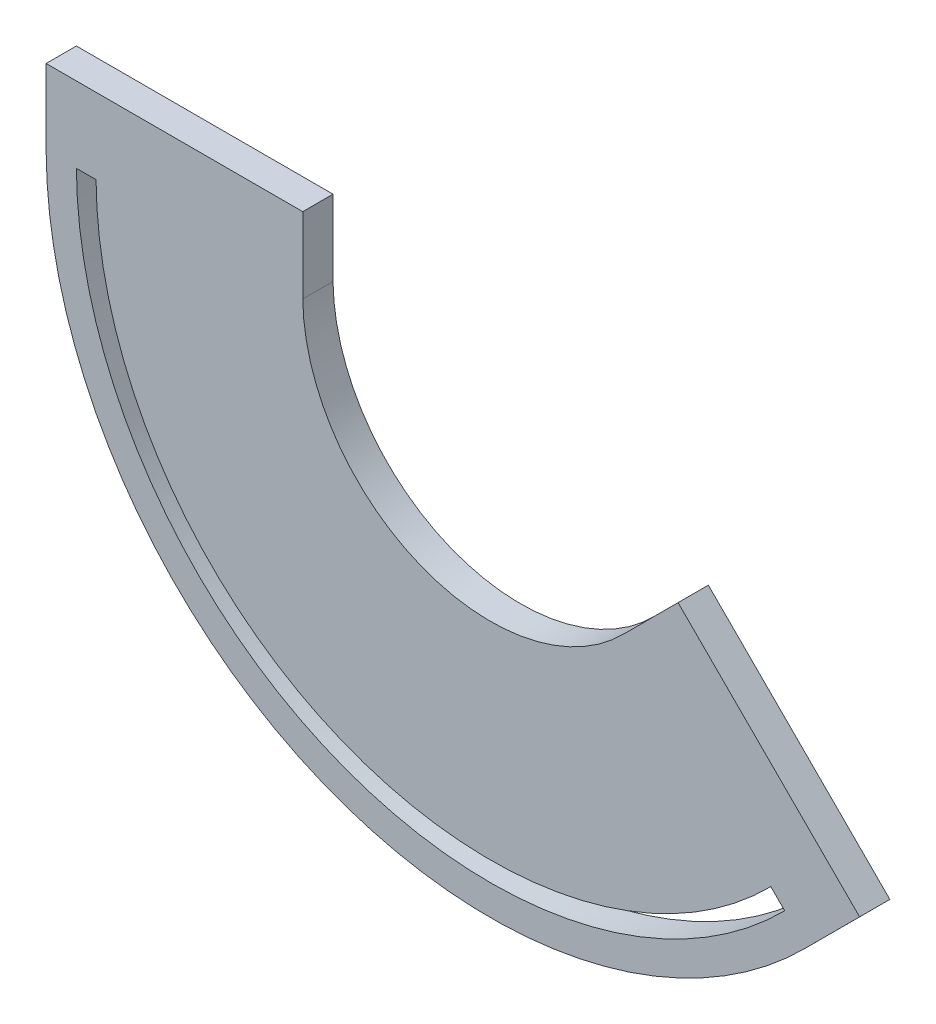
SolidWorks part; units mm, degrees
ref_plane "Front Plane" through (0, 0, 0) normal (0, 0, 1) x (1, 0, 0)
ref_plane "Top Plane" through (0, 0, 0) normal (0, 1, 0) x (1, 0, 0)
ref_plane "Right Plane" through (0, 0, 0) normal (1, 0, 0) x (0, 0, -1)
sketch "Sketch2" plane through (0, 0, 0) normal (0, 0, 1) x (1, 0, 0)
  line L0 (22.5377, -22.0011) -> (53.0117, -52.4532) construction
  line L1 (-74.575, -0.3794) -> (-31.4937, -0.3794) construction
  line L2 (22.5377, -22.0011) -> (31.5148, -13.0176)
  line L3 (31.5148, -13.0176) -> (61.9887, -43.4698)
  line L4 (53.0117, -52.4532) -> (61.9887, -43.4698)
  line L6 (-74.575, -0.3794) -> (-31.4937, -0.3794) construction
  line L7 (-74.575, -0.3794) -> (-74.575, 12.3206)
  line L8 (-74.575, 12.3206) -> (-31.4937, 12.3206)
  line L9 (-31.4937, -0.3794) -> (-31.4937, 12.3206)
  arc A0 (-31.4937, -0.3794) -> (22.5377, -22.0011) centre (0, 0) ccw
  arc A1 (-74.575, -0.3794) -> (53.0117, -52.4532) centre (0, 0) ccw
  dimension "D2" = 74.576
  dimension "D1" = 31.496
  dimension "D3" = 12.7
  dimension "D4" = 12.7
extrude "Boss-Extrude3" add sketch "Sketch2" along normal blind 5.08
sketch "Sketch5" plane through (0, 0, 5.08) normal (0, 0, 1) x (1, 0, 0)
  line L0 (-74.575, -0.3794) -> (-31.4937, -0.3794) construction
  line L1 (53.0117, -52.4532) -> (22.5377, -22.0011) construction
  line L2 (-69.495, -0.3794) -> (-66.193, -0.3794)
  line L3 (47.0826, -46.5284) -> (49.4183, -48.8624)
  arc A0 (-69.495, -0.3794) -> (49.4183, -48.8624) centre (0, 0) ccw
  arc A1 (-66.193, -0.3794) -> (47.0826, -46.5284) centre (0, 0) ccw
  dimension "D1" = 5.08
  dimension "D2" = 3.302
extrude "Cut-Extrude1" cut sketch "Sketch5" against normal through all
equation "\"FoamCore\" = \".2\""
equation "\"MDF\" = \".2\""
equation "\"GMaterial\"= \".2\""
equation "\"PVCMountDiameter\" = \"0.5in\""
equation "\"PVCMountDistanceToEdge\" = \"0.5\""
equation "\"PVCThickness\" = \"0.13in\""
equation "\"PVCDiameter\" = 1.5in"
equation "\"BaseWidth\" = \"8in\""
equation "\"BaseLength\" = \"10in\""
equation "\"BallDiameter\" = \"38mm\""
equation "\"BaseGap\" = \"4in\""
equation "\"FunnelTopDiameter\" = \"8in\""
equation "\"FunnelTopDepth\" = \"0.5in\""
equation "\"BallGap\" = \"0.1in\""
equation "\"FunnelLength\" = 3in"
equation "\"FunnelMaterial\" = 0.1in"
equation "\"FunnelLowerDiameter\" = 1.9in"
equation "\"FunnelDepth\" = 1.5in"
equation "\"FunnelBendLength\" = 2*pi*\"FunnelLowerDiameter\"/2*135"
equation "\"AmmoFeederLength\" = 1.5in + 76mm"
equation "\"WheelThickness\" = 0.5in"
equation "\"LauncherWheelDiameter\" = 76mm"
equation "\"MotorFrontLength\" = 0.95in"
equation "\"MotorBodyTotalLength\" = 2.03in"
equation "\"MotorFrontDiameter\" = 1.5in"
equation "\"MotorLowerDriveshaftDiameter\" = 0.46in"
equation "\"MotorLowerDriveshaftThickness\" = 0.25in"
equation "\"MotorFullDriveshaftLength\" = 0.78in"
equation "\"MotorDriveshaftDiameter\" = 0.23in"
equation "\"MotorDriveshaftFlatThickness\" = 0.2in"
equation "\"MotorRearDiameter\" = 31.9mm"
equation "\"MotorDriveshaftBottomToTop\" = 31.1mm"
equation "\"MotorFlatDriveshaftLength\" = 11.7mm"
equation "\"MotorDistanceBetweenLowerandTopHoles\" = 0.5in"
equation "\"MotorMountsDistanceFromEdge\" = 0.06in"
equation "\"MotorScrewMountDiameter\" = 0.1in"
equation "\"MotorScrewMountDepth\" = 0.13in"
equation "\"HBRidgeScrewHoleDeep\" = 0.18in"
equation "\"MotorMountWidth\" = \"1.61in\""
equation "\"MotorMountLength\" = \"1.58in\""
equation "\"MotorMountToEdgeGap\" = \"3.3mm\""
equation "\"MotorMountToInsideEdgeGap\" = \"6.5mm\""
equation "\"MotorMountToMountWidthGap\" = \"25.8mm\""
equation "\"MotorMountToMountLengthGap\" = \"20.5mm\""
equation "\"MotorMountMaterialThickness\" = 1.6mm"
equation "\"MotorMountBaseScrewholeDiameter\" = 3.8mm"
equation "\"MotorMountBaseDistancebetweenHoles\" = 0.8in"
equation "\"MotorMountHeight\" = 1.85in"
equation "\"HBridgeWidth\" = 2.25in"
equation "\"HBridgeLength\" = 1.40in"
equation "\"UnoWidth\" = 3.13in"
equation "\"UnoLength\" = 3.06in"
equation "\"BatteryWidth\" = 1.15in"
equation "\"BatteryLength\" = 3.86in"
equation "\"ScrewDiameter\" = 2.7mm"
equation "\"MotorMountFaceScrewtoBase\" = 0.46in"
equation "\"MotorMountFaceDistanceBetweenScrews\" = 0.95in"
equation "\"MotorMountFaceMiddletoEdge\" = 0.16in"
equation "\"MotorMountFaceBottomtoEdge\" = 0.42in"
equation "\"MotorMountCenterholeHeight\" = 1.04in"
equation "\"MotorMountCenterholetoEdge\" = 0.25in"
equation "\"MovingWheelDiameter\" = 76mm"
equation "\"MovingWheelThickness\" = 0.5in"
equation "\"BraceLength\" = 1in"
equation "\"BraceVerticalOffset\" = 3.5in"
equation "\"BraceHorizontalOffset\" = 2.5in"
equation "\"BaseToBaseDistance\" = 7in"
equation "\"PVCOutsideDiameter\" = \"PVCDiameter\" + 2*\"PVCThickness\""
equation "\"Distancebetweenwalls\" = 6in"
equation "\"Slidewidth\" = 0.3in"
equation "\"Slidelength\" = 0.8in"
equation "\"Bottomtofloor\" = 0.53in"
equation "\"tabdistance\" = 0.2in"
equation "\"tabwidth\" = 0.3in"
equation "\"ShooterWheelDiameter\"= 1.88in"
equation "\"ShooterWheelThick\"= 1.03in"
equation "\"ShooterRubberThick\"= 0.3in"
equation "\"3DMaterial\" = \"PVCThickness\""
equation "\"D2@Sketch2\"= (\"ShooterWheelDiameter\"/2) + \"ShooterRubberThick\"+ \"BallDiameter\"+\"MDF\""
equation "\"D1@Sketch2\"=(\"ShooterWheelDiameter\"/2) + \"ShooterRubberThick\""
equation "\"D3@Sketch2\"=0.5"
equation "\"D1@Boss-Extrude3\"=\"MDF\""
equation "\"D1@Sketch5\"=\"MDF\""
equation "\"D2@Sketch5\"=\"3DMaterial\""
